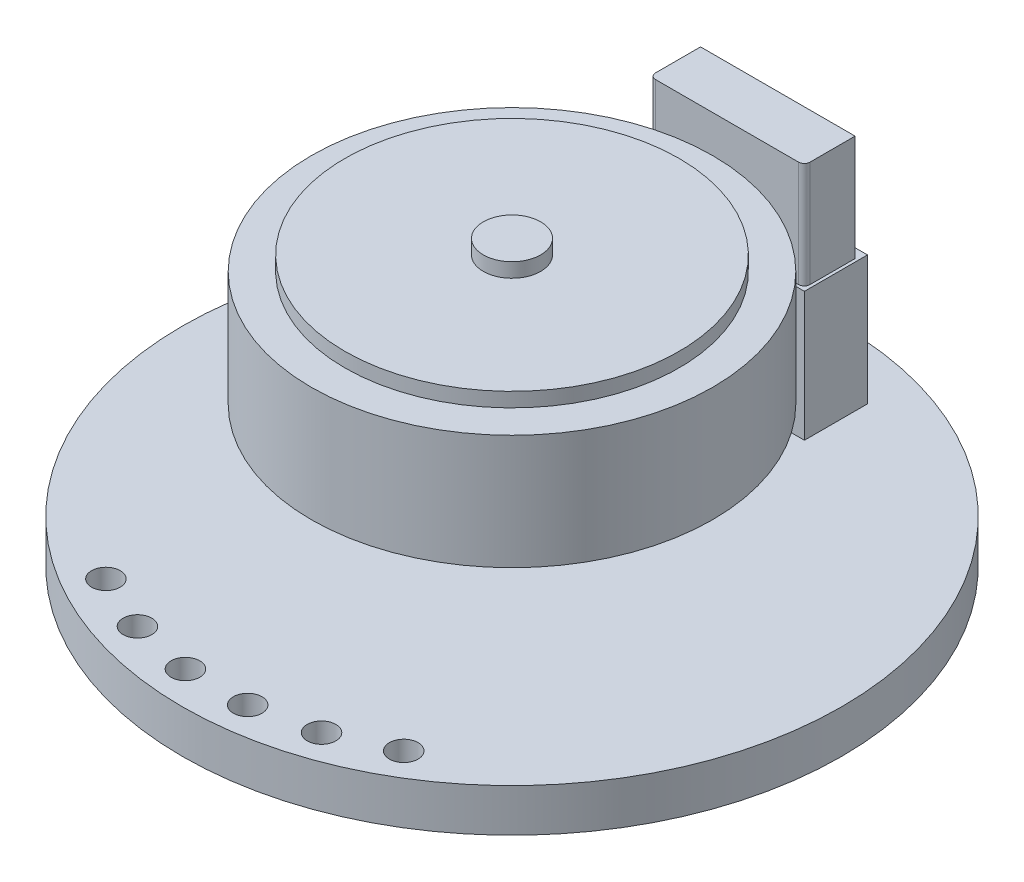
SolidWorks part; units mm, degrees
ref_plane "Plano frontal" through (0, 0, 0) normal (0, 0, 1) x (1, 0, 0)
ref_plane "Plano superior" through (0, 0, 0) normal (0, 1, 0) x (1, 0, 0)
ref_plane "Plano direito" through (0, 0, 0) normal (1, 0, 0) x (0, 0, -1)
sketch "Esboço1" plane through (0, 0, 0) normal (0, 1, 0) x (1, 0, 0)
  circle A0 centre (0, 0) radius 11.5
  dimension "D1" = 23
extrude "Ressalto-extrusão1" add sketch "Esboço1" along normal blind 1.5
sketch "Esboço2" plane through (0, 1.5, 0) normal (0, 1, 0) x (1, 0, 0)
  line L1 (-2.8, 9.6) -> (2.8, 9.6)
  line L2 (-2.8, 9.6) -> (-2.8, 7.4)
  line L3 (-2.8, 7.4) -> (2.8, 7.4)
  line L4 (2.8, 9.6) -> (2.8, 7.4)
  line L5 (-2.8, 9.6) -> (2.8, 7.4) construction
  line L6 (-2.8, 7.4) -> (2.8, 9.6) construction
  point P0 (0, 8.5)
  dimension "D1" = 8.5
  dimension "D2" = 5.6
  dimension "D3" = 2.2
extrude "Ressalto-extrusão2" add sketch "Esboço2" along normal blind 4.5
sketch "Esboço3" plane through (0, 6, 0) normal (0, 1, 0) x (1, 0, 0)
  line L1 (-2.6951, 9.2715) -> (2.6951, 9.2715)
  line L2 (-2.6951, 9.2715) -> (-2.6951, 7.7)
  line L3 (-2.4951, 7.5) -> (2.4951, 7.5)
  line L4 (2.6951, 9.2715) -> (2.6951, 7.7)
  line L5 (-2.6951, 9.2715) -> (2.6951, 7.5) construction
  line L6 (-2.6951, 7.5) -> (2.6951, 9.2715) construction
  line L7 (0, 9.6) -> (0, 7.4) construction
  line L8 (2.8, 9.6) -> (-2.8, 9.6) construction
  line L9 (-2.8, 7.4) -> (2.8, 7.4) construction
  arc A0 (2.4951, 7.5) -> (2.6951, 7.7) centre (2.4951, 7.7) ccw
  arc A1 (-2.6951, 7.7) -> (-2.4951, 7.5) centre (-2.4951, 7.7) ccw
  point P0 (0, 8.3858)
  dimension "D1" = 0.2
  dimension "D2" = 0.1
extrude "Ressalto-extrusão3" add sketch "Esboço3" along normal blind 3.7
sketch "Esboço4" plane through (0, 1.5, 0) normal (0, 1, 0) x (1, 0, 0)
  circle A0 centre (0, 0) radius 1
  dimension "D1" = 2
extrude "Ressalto-extrusão4" add sketch "Esboço4" along normal blind 3.4
sketch "Esboço5" plane through (0, 4.9, 0) normal (0, 1, 0) x (1, 0, 0)
  circle A0 centre (0, 0) radius 7
  dimension "D1" = 14
extrude "Ressalto-extrusão5" add sketch "Esboço5" along normal blind 4
sketch "Esboço6" plane through (0, 8.9, 0) normal (0, 1, 0) x (1, 0, 0)
  circle A0 centre (0, 0) radius 5.83
extrude "Ressalto-extrusão6" add sketch "Esboço6" along normal blind 0.5
sketch "Esboço7" plane through (0, 9.4, 0) normal (0, 1, 0) x (1, 0, 0)
  circle A0 centre (0, 0) radius 1
  dimension "D1" = 2
extrude "Ressalto-extrusão7" add sketch "Esboço7" along normal blind 0.5
sketch "Esboço8" plane through (0, 1.5, 0) normal (0, 1, 0) x (1, 0, 0)
  line L0 (0, 0) -> (0, -10.3053) construction
  line L2 (-1.0859, -10.3053) -> (1.0859, -10.3053) construction
  circle A2 centre (5.1942, -8.9704) radius 0.5
  circle A3 centre (3.2102, -9.8537) radius 0.5
  circle A4 centre (1.0859, -10.3053) radius 0.5
  circle A5 centre (-1.0859, -10.3053) radius 0.5
  circle A6 centre (-3.2102, -9.8537) radius 0.5
  circle A7 centre (-5.1942, -8.9704) radius 0.5
  point P15 (0, 0.0262)
  dimension "D1" = 6
extrude "Corte-extrusão1" cut sketch "Esboço8" against normal through all
